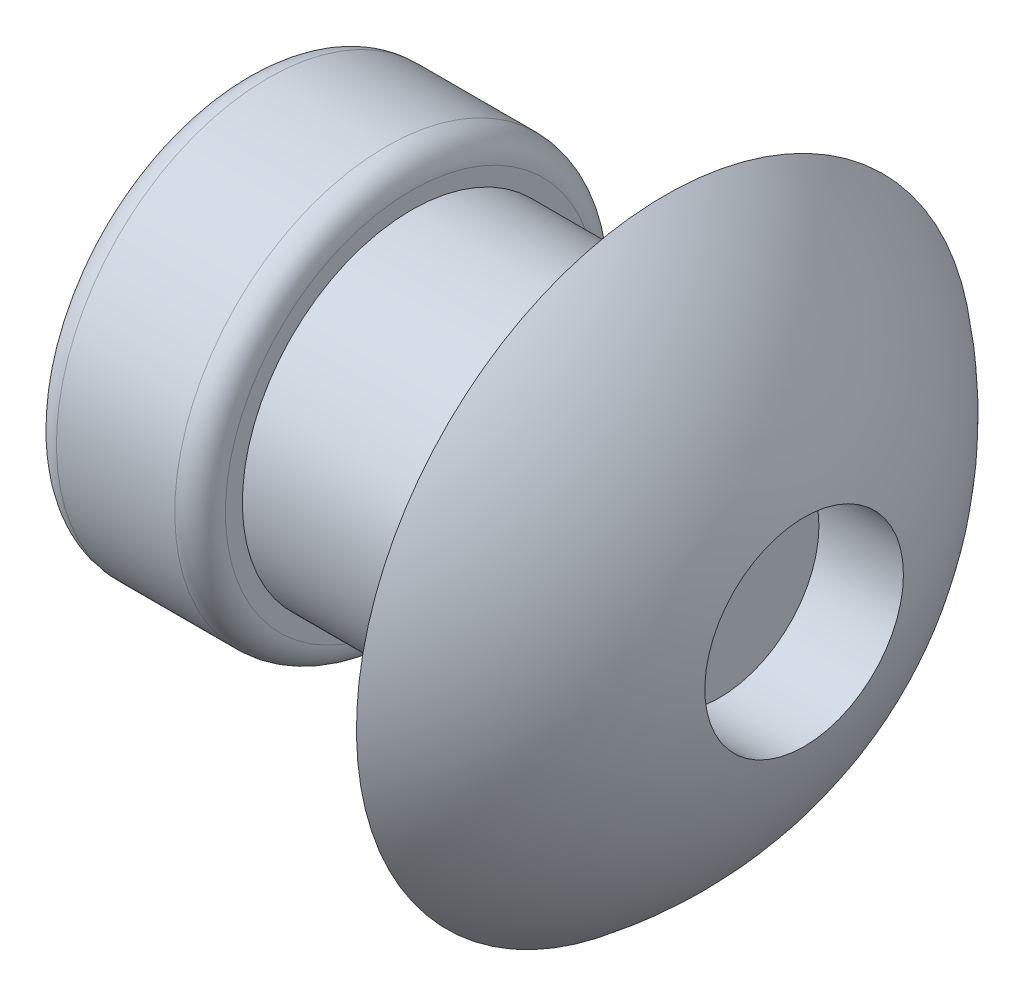
SolidWorks part; units mm, degrees
material "Сталь 20 ГОСТ 1050-88"
ref_plane "Front" through (0, 0, 0) normal (0, 0, 1) x (1, 0, 0)
ref_plane "Top" through (0, 0, 0) normal (0, 1, 0) x (1, 0, 0)
ref_plane "Right" through (0, 0, 0) normal (1, 0, 0) x (0, 0, -1)
sketch "Sketch1" plane through (-11.6035, 14.7235, 0) normal (0, 0, 1) x (0, -1, 0)
  line L0 (16.9235, 12.1035) -> (16.5982, 12.1035)
  line L1 (16.7235, 14.1035) -> (16.7235, 17.1035)
  line L2 (16.7235, 17.1035) -> (18.3735, 17.1035)
  line L3 (14.7235, 33.8377) -> (14.7235, 9.0903) construction
  line L4 (15.8985, 18.7509) -> (15.8985, 46.7509)
  line L5 (15.8985, 46.7509) -> (14.7235, 46.7509)
  line L6 (14.7235, 11.6035) -> (14.7235, 46.7509)
  line L7 (15.8985, 11.6035) -> (14.7235, 11.6035)
  line L8 (16.7235, 14.1035) -> (16.9235, 14.1035)
  line L9 (17.2235, 13.8035) -> (17.2235, 12.4035)
  line L10 (14.7235, 18.9035) -> (13.7235, 18.9035) construction
  arc A0 (18.3735, 17.1035) -> (15.8985, 18.7509) centre (14.7235, 14.3028) ccw
  arc A1 (16.5982, 12.1035) -> (15.8985, 11.6035) centre (15.7235, 12.588) cw
  arc A2 (17.2235, 12.4035) -> (16.9235, 12.1035) centre (16.9235, 12.4035) cw
  arc A3 (16.9235, 14.1035) -> (17.2235, 13.8035) centre (16.9235, 13.8035) cw
  arc A4 (15.8985, 18.7509) -> (14.7235, 18.9035) centre (14.7235, 14.3028) ccw construction
  dimension "D5" = 0.3
  dimension "D2" = 1
  dimension "d" = 4
  dimension "dk" = 7.3
  dimension "d1" = 2.35
  dimension "l1" = 28
  dimension "D4" = 5
  dimension "l" = 3
  dimension "l2" = 2
  dimension "D7" = 0.5
  dimension "K" = 1.8
  dimension "D3" = 1
revolve "Base-Revolve" add sketch "Sketch1" angle 360 about L3
fillet "Fillet1" radius 0.5 1 edges at (5.5, 2, 0)
chamfer "Chamfer1" distance 2.35 angle 15 1 edges at (35.1474, 1.175, 0)
sketch "Эскиз1" plane through (0, 0, 0) normal (0, 1, 0) x (1, 0, 0)
  line L0 (35.1474, -0.5453) -> (35.1474, 0.5453) construction
  line L1 (6.1474, 1.175) -> (35.1474, 1.175)
  line L2 (6.1474, 1.175) -> (6.1474, 0)
  line L3 (35.1474, 0) -> (6.1474, 0)
  line L4 (35.1474, 1.175) -> (35.1474, 0)
  line L6 (32.7974, 1.175) -> (7.1474, 1.175) construction
  line L7 (7.1474, -1.175) -> (7.1474, 1.175) construction
  line L8 (35.1474, 0) -> (6.1474, 0) construction
  dimension "D1" = 1
revolve "Вырез-Повернуть1" cut sketch "Эскиз1" angle 360 about L8
sketch "Эскиз2" plane through (0, 0, 0) normal (0, 1, 0) x (1, 0, 0)
  line L0 (2.2, 2.5) -> (0.8, 2.5) construction
  line L1 (-1.5, 2.5) -> (2.5, 2.5)
  line L2 (-1.5, 2.5) -> (-1.5, -2.5)
  line L3 (-1.5, -2.5) -> (2.5, -2.5)
  line L4 (2.5, 2.5) -> (2.5, -2.5)
  line L6 (2.5, -2) -> (2.5, 2) construction
  line L7 (0.8, -2.5) -> (2.2, -2.5) construction
  dimension "D1" = 4
extrude "Вырез-Вытянуть1" [suppressed] cut sketch "Эскиз2" against normal through all both and the other way through all
equation "\"D1@Chamfer1\" = \"d1@Sketch1\""
